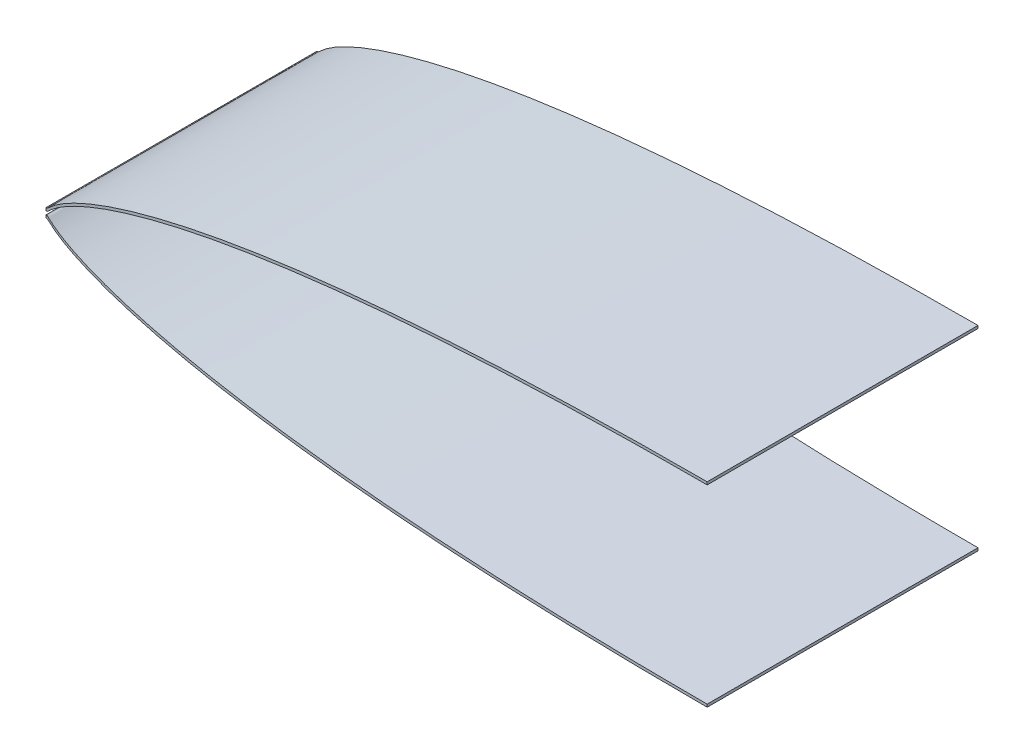
SolidWorks part; units mm, degrees
ref_plane "Front Plane" through (0, 0, 0) normal (0, 0, 1) x (1, 0, 0)
ref_plane "Top Plane" through (0, 0, 0) normal (0, 1, 0) x (1, 0, 0)
ref_plane "Right Plane" through (0, 0, 0) normal (1, 0, 0) x (0, 0, -1)
curve "Curve1"
  spline degree 3 poles (0, 3.2907, 0) (0.0125, 3.2908, 0) (0.0375, 3.2908, 0) (0.0751, 3.2915, 0) (0.1126, 3.2926, 0) (0.1501, 3.2941, 0) (0.1876, 3.296, 0) (0.225, 3.2984, 0) (0.2625, 3.3011, 0) (0.2999, 3.3043, 0) (0.3372, 3.308, 0) (0.3745, 3.312, 0) (0.4118, 3.3165, 0) (0.449, 3.3214, 0) (0.4862, 3.3268, 0) (0.5232, 3.3325, 0) (0.5603, 3.3387, 0) (0.5972, 3.3453, 0) (0.6341, 3.3523, 0) (0.6709, 3.3598, 0) (0.7076, 3.3676, 0) (0.7442, 3.3759, 0) (0.7807, 3.3846, 0) (0.8171, 3.3937, 0) (0.8534, 3.4032, 0) (0.8896, 3.4132, 0) (0.9257, 3.4235, 0) (0.9616, 3.4343, 0) (0.9975, 3.4455, 0) (1.0332, 3.457, 0) (1.0688, 3.469, 0) (1.1042, 3.4814, 0) (1.1395, 3.4942, 0) (1.1746, 3.5074, 0) (1.2096, 3.521, 0) (1.2444, 3.535, 0) (1.2791, 3.5494, 0) (1.3136, 3.5642, 0) (1.3479, 3.5794, 0) (1.3821, 3.5949, 0) (1.416, 3.6109, 0) (1.4498, 3.6272, 0) (1.4834, 3.644, 0) (1.5168, 3.6611, 0) (1.55, 3.6786, 0) (1.583, 3.6964, 0) (1.6158, 3.7147, 0) (1.6484, 3.7333, 0) (1.6808, 3.7523, 0) (1.713, 3.7716, 0) (1.7449, 3.7914, 0) (1.7766, 3.8114, 0) (1.8081, 3.8319, 0) (1.8393, 3.8527, 0) (1.8703, 3.8738, 0) (1.9011, 3.8953, 0) (1.9316, 3.9172, 0) (1.9619, 3.9394, 0) (1.9919, 3.962, 0) (2.0216, 3.9848, 0) (2.0511, 4.0081, 0) (2.0803, 4.0316, 0) (2.1093, 4.0555, 0) (2.138, 4.0797, 0) (2.1663, 4.1043, 0) (2.1945, 4.1292, 0) (3.4207, 5.2445, 0) (5.0817, 6.7606, 0) (7.1488, 8.5925, 0) (8.3815, 9.6582, 0) (9.5428, 10.6394, 0) (10.6953, 11.5907, 0) (11.8675, 12.5359, 0) (13.0769, 13.4885, 0) (14.3362, 14.4574, 0) (15.6557, 15.4487, 0) (17.0445, 16.4676, 0) (18.5115, 17.5183, 0) (20.0649, 18.6042, 0) (21.7134, 19.7289, 0) (23.4658, 20.8954, 0) (25.3314, 22.1067, 0) (27.3198, 23.3658, 0) (29.4415, 24.6756, 0) (31.7075, 26.039, 0) (34.1296, 27.459, 0) (36.7207, 28.9386, 0) (39.4943, 30.4808, 0) (42.4655, 32.0887, 0) (45.6503, 33.7655, 0) (49.0661, 35.5144, 0) (52.7319, 37.3389, 0) (56.6681, 39.2423, 0) (60.8971, 41.2281, 0) (65.4433, 43.2998, 0) (70.3331, 45.4611, 0) (75.5954, 47.7156, 0) (81.2617, 50.0671, 0) (87.3665, 52.5193, 0) (93.9473, 55.076, 0) (101.0454, 57.7408, 0) (108.7059, 60.5175, 0) (116.9781, 63.4096, 0) (125.9164, 66.4206, 0) (135.5801, 69.5536, 0) (146.0347, 72.8118, 0) (157.3521, 76.1977, 0) (169.6115, 79.7136, 0) (182.9002, 83.3612, 0) (197.3143, 87.1414, 0) (212.9602, 91.0545, 0) (229.9553, 95.0995, 0) (248.4293, 99.2745, 0) (268.5263, 103.5759, 0) (290.4056, 107.9984, 0) (314.2443, 112.5345, 0) (340.239, 117.1743, 0) (368.6084, 121.9046, 0) (399.5962, 126.7089, 0) (433.4739, 131.5661, 0) (470.5448, 136.4503, 0) (511.1479, 141.3293, 0) (555.6626, 146.1639, 0) (604.5141, 150.9062, 0) (658.1796, 155.4986, 0) (717.1955, 159.8712, 0) (782.1656, 163.9405, 0) (853.7702, 167.605, 0) (932.7777, 170.7489, 0) (1020.0568, 173.2087, 0) (1116.5913, 174.8986, 0) (1184.1432, 175.1146, 0) (1219.6371, 175.2281, 0) knots 0 0 0 0 0.00003 0.00006 0.00009 0.000121 0.000151 0.000181 0.000211 0.000241 0.000271 0.000302 0.000332 0.000362 0.000392 0.000422 0.000452 0.000482 0.000513 0.000543 0.000573 0.000603 0.000633 0.000663 0.000694 0.000724 0.000754 0.000784 0.000814 0.000844 0.000875 0.000905 0.000935 0.000965 0.000995 0.001025 0.001055 0.001086 0.001116 0.001146 0.001176 0.001206 0.001236 0.001267 0.001297 0.001327 0.001357 0.001387 0.001417 0.001447 0.001478 0.001508 0.001538 0.001568 0.001598 0.001628 0.001659 0.001689 0.001719 0.001749 0.001779 0.001809 0.00184 0.00187 0.0019 0.00193 0.00196 0.005895 0.00735 0.008617 0.009823 0.011015 0.012219 0.013452 0.014726 0.016049 0.01743 0.018877 0.020398 0.021999 0.023687 0.025472 0.02736 0.02936 0.031482 0.033734 0.036127 0.038673 0.041383 0.04427 0.047348 0.050633 0.05414 0.057887 0.061894 0.066181 0.070773 0.075692 0.080968 0.086629 0.092709 0.099242 0.106269 0.113831 0.121976 0.130755 0.140225 0.150448 0.161495 0.173439 0.186366 0.200367 0.215546 0.232016 0.249904 0.269348 0.290505 0.313548 0.33867 0.366087 0.396038 0.428794 0.464656 0.503962 0.547094 0.594478 0.646597 0.703997 0.767291 0.837178 0.914448 1 1 1 1
sketch "Sketch2" plane through (0, 0, 0) normal (0, 0, 1) x (1, 0, 0)
  line L0 (0, 3.2907) -> (-1, 3.2907)
  line L1 (-1, 3.2907) -> (-1, 8.2907)
  line L2 (-1, 8.2907) -> (0, 8.2907)
  line L3 (1219.6371, 175.2281) -> (1219.6371, 180.2281)
  spline S0 degree 3 poles (7.4104, -1990.2716) (-7.0667, 10.3783) (-3.4696, 3.2286) (0.0751, 3.2915) (0.1626, 3.294) (0.3125, 3.3034) (0.5609, 3.3347) (0.8426, 3.3951) (1.141, 3.49) (1.418, 3.6068) (1.6831, 3.7484) (1.9029, 3.8929) (2.0417, 3.9998) (2.1093, 4.0555) (2.138, 4.0797) (2.1663, 4.1043) (2.1945, 4.1292) (3.4207, 5.2445) (5.0817, 6.7606) (7.1488, 8.5925) (8.3815, 9.6582) (9.5428, 10.6394) (10.6953, 11.5907) (11.8675, 12.5359) (13.0769, 13.4885) (14.3362, 14.4574) (15.6557, 15.4487) (17.0445, 16.4676) (18.5115, 17.5183) (20.0649, 18.6042) (21.7134, 19.7289) (23.4658, 20.8954) (25.3314, 22.1067) (27.3198, 23.3658) (29.4415, 24.6756) (31.7075, 26.039) (34.1296, 27.459) (36.7207, 28.9386) (39.4943, 30.4808) (42.4655, 32.0887) (45.6503, 33.7655) (49.0661, 35.5144) (52.7319, 37.3389) (56.6681, 39.2423) (60.8971, 41.2281) (65.4433, 43.2998) (70.3331, 45.4611) (75.5954, 47.7156) (81.2617, 50.0671) (87.3665, 52.5193) (93.9473, 55.076) (101.0454, 57.7408) (108.7059, 60.5175) (116.9781, 63.4096) (125.9164, 66.4206) (135.5801, 69.5536) (146.0347, 72.8118) (157.3521, 76.1977) (169.6115, 79.7136) (182.9002, 83.3612) (197.3143, 87.1414) (212.9602, 91.0545) (229.9553, 95.0995) (248.4293, 99.2745) (268.5263, 103.5759) (290.4056, 107.9984) (314.2443, 112.5345) (340.239, 117.1743) (368.6084, 121.9046) (399.5962, 126.7089) (433.4739, 131.5661) (470.5448, 136.4503) (511.1479, 141.3293) (555.6626, 146.1639) (604.5141, 150.9062) (658.1796, 155.4986) (717.1955, 159.8712) (782.1656, 163.9405) (853.7702, 167.605) (932.7777, 170.7489) (1020.0568, 173.2087) (1661.5833, 184.4391) (2274.8262, 115.6805) (2846.2209, 1146.676) knots -0.008454 -0.008454 -0.008454 -0.008454 0.00003 0.00006 0.00009 0.000241 0.000422 0.000694 0.000935 0.001176 0.001417 0.001659 0.001809 0.00184 0.00187 0.0019 0.00193 0.00196 0.005895 0.00735 0.008617 0.009823 0.011015 0.012219 0.013452 0.014726 0.016049 0.01743 0.018877 0.020398 0.021999 0.023687 0.025472 0.02736 0.02936 0.031482 0.033734 0.036127 0.038673 0.041383 0.04427 0.047348 0.050633 0.05414 0.057887 0.061894 0.066181 0.070773 0.075692 0.080968 0.086629 0.092709 0.099242 0.106269 0.113831 0.121976 0.130755 0.140225 0.150448 0.161495 0.173439 0.186366 0.200367 0.215546 0.232016 0.249904 0.269348 0.290505 0.313548 0.33867 0.366087 0.396038 0.428794 0.464656 0.503962 0.547094 0.594478 0.646597 0.703997 0.767291 0.837178 0.914448 2.313773 2.313773 2.313773 2.313773 only from (0, 3.2907) to (1219.6371, 175.2281) construction
  spline S1 degree 3 poles (0, 3.2907) (0.0125, 3.2908) (0.0375, 3.2908) (0.0751, 3.2915) (0.1626, 3.294) (0.3125, 3.3034) (0.5609, 3.3347) (0.8426, 3.3951) (1.141, 3.49) (1.418, 3.6068) (1.6831, 3.7484) (1.9029, 3.8929) (2.0417, 3.9998) (2.1093, 4.0555) (2.138, 4.0797) (2.1663, 4.1043) (2.1945, 4.1292) (3.4207, 5.2445) (5.0817, 6.7606) (7.1488, 8.5925) (8.3815, 9.6582) (9.5428, 10.6394) (10.6953, 11.5907) (11.8675, 12.5359) (13.0769, 13.4885) (14.3362, 14.4574) (15.6557, 15.4487) (17.0445, 16.4676) (18.5115, 17.5183) (20.0649, 18.6042) (21.7134, 19.7289) (23.4658, 20.8954) (25.3314, 22.1067) (27.3198, 23.3658) (29.4415, 24.6756) (31.7075, 26.039) (34.1296, 27.459) (36.7207, 28.9386) (39.4943, 30.4808) (42.4655, 32.0887) (45.6503, 33.7655) (49.0661, 35.5144) (52.7319, 37.3389) (56.6681, 39.2423) (60.8971, 41.2281) (65.4433, 43.2998) (70.3331, 45.4611) (75.5954, 47.7156) (81.2617, 50.0671) (87.3665, 52.5193) (93.9473, 55.076) (101.0454, 57.7408) (108.7059, 60.5175) (116.9781, 63.4096) (125.9164, 66.4206) (135.5801, 69.5536) (146.0347, 72.8118) (157.3521, 76.1977) (169.6115, 79.7136) (182.9002, 83.3612) (197.3143, 87.1414) (212.9602, 91.0545) (229.9553, 95.0995) (248.4293, 99.2745) (268.5263, 103.5759) (290.4056, 107.9984) (314.2443, 112.5345) (340.239, 117.1743) (368.6084, 121.9046) (399.5962, 126.7089) (433.4739, 131.5661) (470.5448, 136.4503) (511.1479, 141.3293) (555.6626, 146.1639) (604.5141, 150.9062) (658.1796, 155.4986) (717.1955, 159.8712) (782.1656, 163.9405) (853.7702, 167.605) (932.7777, 170.7489) (1020.0568, 173.2087) (1116.5913, 174.8986) (1184.1432, 175.1146) (1219.6371, 175.2281) knots 0 0 0 0 0.00003 0.00006 0.00009 0.000241 0.000422 0.000694 0.000935 0.001176 0.001417 0.001659 0.001809 0.00184 0.00187 0.0019 0.00193 0.00196 0.005895 0.00735 0.008617 0.009823 0.011015 0.012219 0.013452 0.014726 0.016049 0.01743 0.018877 0.020398 0.021999 0.023687 0.025472 0.02736 0.02936 0.031482 0.033734 0.036127 0.038673 0.041383 0.04427 0.047348 0.050633 0.05414 0.057887 0.061894 0.066181 0.070773 0.075692 0.080968 0.086629 0.092709 0.099242 0.106269 0.113831 0.121976 0.130755 0.140225 0.150448 0.161495 0.173439 0.186366 0.200367 0.215546 0.232016 0.249904 0.269348 0.290505 0.313548 0.33867 0.366087 0.396038 0.428794 0.464656 0.503962 0.547094 0.594478 0.646597 0.703997 0.767291 0.837178 0.914448 1 1 1 1
  spline S2 degree 3 poles (0, 8.2907) (0.0125, 8.2908) (0.0375, 8.2908) (0.0751, 8.2915) (0.1626, 8.294) (0.3125, 8.3034) (0.5609, 8.3347) (0.8426, 8.3951) (1.141, 8.49) (1.418, 8.6068) (1.6831, 8.7484) (1.9029, 8.8929) (2.0417, 8.9998) (2.1093, 9.0555) (2.138, 9.0797) (2.1663, 9.1043) (2.1945, 9.1292) (3.4207, 10.2445) (5.0817, 11.7606) (7.1488, 13.5925) (8.3815, 14.6582) (9.5428, 15.6394) (10.6953, 16.5907) (11.8675, 17.5359) (13.0769, 18.4885) (14.3362, 19.4574) (15.6557, 20.4487) (17.0445, 21.4676) (18.5115, 22.5183) (20.0649, 23.6042) (21.7134, 24.7289) (23.4658, 25.8954) (25.3314, 27.1067) (27.3198, 28.3658) (29.4415, 29.6756) (31.7075, 31.039) (34.1296, 32.459) (36.7207, 33.9386) (39.4943, 35.4808) (42.4655, 37.0887) (45.6503, 38.7655) (49.0661, 40.5144) (52.7319, 42.3389) (56.6681, 44.2423) (60.8971, 46.2281) (65.4433, 48.2998) (70.3331, 50.4611) (75.5954, 52.7156) (81.2617, 55.0671) (87.3665, 57.5193) (93.9473, 60.076) (101.0454, 62.7408) (108.7059, 65.5175) (116.9781, 68.4096) (125.9164, 71.4206) (135.5801, 74.5536) (146.0347, 77.8118) (157.3521, 81.1977) (169.6115, 84.7136) (182.9002, 88.3612) (197.3143, 92.1414) (212.9602, 96.0545) (229.9553, 100.0995) (248.4293, 104.2745) (268.5263, 108.5759) (290.4056, 112.9984) (314.2443, 117.5345) (340.239, 122.1743) (368.6084, 126.9046) (399.5962, 131.7089) (433.4739, 136.5661) (470.5448, 141.4503) (511.1479, 146.3293) (555.6626, 151.1639) (604.5141, 155.9062) (658.1796, 160.4986) (717.1955, 164.8712) (782.1656, 168.9405) (853.7702, 172.605) (932.7777, 175.7489) (1020.0568, 178.2087) (1116.5913, 179.8986) (1184.1432, 180.1146) (1219.6371, 180.2281) knots 0 0 0 0 0.00003 0.00006 0.00009 0.000241 0.000422 0.000694 0.000935 0.001176 0.001417 0.001659 0.001809 0.00184 0.00187 0.0019 0.00193 0.00196 0.005895 0.00735 0.008617 0.009823 0.011015 0.012219 0.013452 0.014726 0.016049 0.01743 0.018877 0.020398 0.021999 0.023687 0.025472 0.02736 0.02936 0.031482 0.033734 0.036127 0.038673 0.041383 0.04427 0.047348 0.050633 0.05414 0.057887 0.061894 0.066181 0.070773 0.075692 0.080968 0.086629 0.092709 0.099242 0.106269 0.113831 0.121976 0.130755 0.140225 0.150448 0.161495 0.173439 0.186366 0.200367 0.215546 0.232016 0.249904 0.269348 0.290505 0.313548 0.33867 0.366087 0.396038 0.428794 0.464656 0.503962 0.547094 0.594478 0.646597 0.703997 0.767291 0.837178 0.914448 1 1 1 1
  dimension "D1" = 1
  dimension "D2" = 5
extrude "Boss-Extrude1" add sketch "Sketch2" along normal mid plane 500
mirror "Mirror2" about plane through (0, 0, 0) normal (0, 1, 0) of bodies 101
